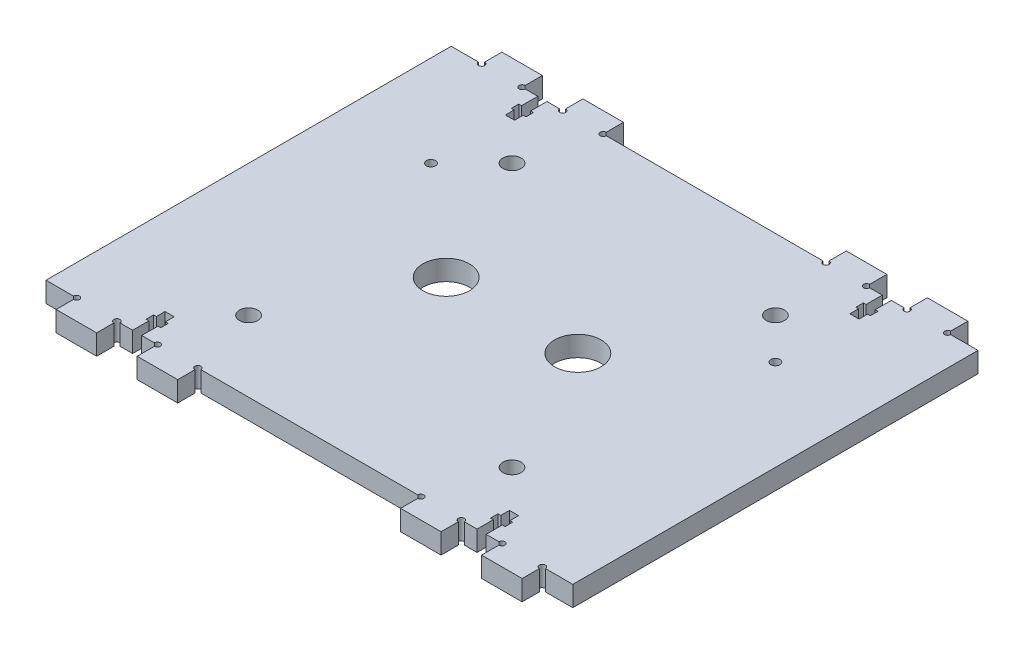
SolidWorks part; units mm, degrees
material "POLICARB. TRANSP."
ref_plane "Front Plane" through (0, 0, 0) normal (0, 0, 1) x (1, 0, 0)
ref_plane "Top Plane" through (0, 0, 0) normal (0, 1, 0) x (1, 0, 0)
ref_plane "Right Plane" through (0, 0, 0) normal (1, 0, 0) x (0, 0, -1)
sketch "Sketch1" plane through (0, 0, 0) normal (0, 1, 0) x (1, 0, 0)
  line L1 (130, 100) -> (-130, 100)
  line L2 (130, 100) -> (130, -100)
  line L3 (130, -100) -> (-130, -100)
  line L4 (-130, 100) -> (-130, -100)
  line L5 (0, -100) -> (0, 100) construction
  line L6 (130, 0) -> (-130, 0) construction
  point P0 (0, 0)
  dimension "D1" = 200
  dimension "D2" = 260
extrude "Extrude1" add sketch "Sketch1" along normal blind 10
sketch "Sketch3" plane through (0, 10, 0) normal (0, 1, 0) x (1, 0, 0)
  line L0 (130, 100) -> (-130, 100) construction
  line L1 (-115, 50) -> (-95, 50)
  line L2 (-115, 50) -> (-115, 40)
  line L3 (-115, 40) -> (-95, 40)
  line L4 (-95, 50) -> (-95, 40)
  line L9 (95, 50) -> (115, 50)
  line L10 (95, 50) -> (95, 40)
  line L11 (95, 40) -> (115, 40)
  line L12 (115, 50) -> (115, 40)
  line L13 (0, 0) -> (0, -100) construction
  line L14 (-130, -100) -> (130, -100) construction
  line L15 (-130, 100) -> (-130, -100) construction
  line L17 (-75, 50) -> (-55, 50)
  line L18 (-75, 50) -> (-75, 40)
  line L19 (-75, 40) -> (-55, 40)
  line L20 (-55, 50) -> (-55, 40)
  line L21 (55, 50) -> (75, 50)
  line L22 (55, 50) -> (55, 40)
  line L23 (55, 40) -> (75, 40)
  line L24 (75, 50) -> (75, 40)
  dimension "D1" = 50
  dimension "D2" = 20
  dimension "D3" = 10
  dimension "D4" = 15
  dimension "D5" = 20
  dimension "D6" = 10
  dimension "D7" = 20
extrude "Extrude2" [suppressed] cut sketch "Sketch3" against normal blind 10
hole_wizard "M4 Clearance Hole1" positions "Sketch4" profile "Sketch5" hole size "M4" standard "DIN" end condition through all
sketch "Sketch4" plane through (0, 10, 0) normal (0, 1, 0) x (1, 0, 0)
  line L0 (0, 0) -> (0, 100) construction
  line L8 (130, 100) -> (-130, 100) construction
  line L14 (-130, 100) -> (-130, -100) construction
  point P0 (-85, 45)
  point P2 (85, 45)
  point P44 (0, 0)
  dimension "D1" = 45
  dimension "D2" = 55
sketch "Sketch5" plane through (-85, 10, -45) normal (1, 0, 0) x (0, 0, 1)
  line L0 (0, 0) -> (0, 10)
  line L1 (0, 10) -> (2.25, 10)
  line L2 (2.25, 10) -> (2.25, 0)
  line L5 (2.25, 0) -> (0, 0)
  line L11 (0, -6.35) -> (0, 107.95) construction
  dimension "Thru Hole Dia." = 4.5
  dimension "Thru Hole Depth" = 10
sketch "Sketch6" [suppressed] plane through (0, 10, 0) normal (0, 1, 0) x (1, 0, 0)
  line L0 (-113.5, 50) -> (-115, 50)
  line L1 (-115, 50) -> (-115, 48.5)
  line L2 (-113.5, 40) -> (-115, 40)
  line L3 (-115, 40) -> (-115, 41.5)
  arc A0 (-115, 41.5) -> (-113.5, 40) centre (-115, 40) ccw
  arc A1 (-113.5, 50) -> (-115, 48.5) centre (-115, 50) ccw
  dimension "D1" = 3
extrude "Extrude3" [suppressed] cut sketch "Sketch6" against normal blind 10
ref_plane "Plane1" [suppressed] through (-105, 0, 0) normal (1, 0, 0) x (0, 0, -1)
mirror "Mirror1" [suppressed] about plane through (-105, 0, 0) normal (1, 0, 0)
ref_plane "Plane2" [suppressed] through (-85, 0, 0) normal (-1, 0, 0) x (0, 0, 1)
mirror "Mirror2" [suppressed] about plane through (-85, 0, 0) normal (-1, 0, 0)
ref_plane "Plane3" through (0, 0, 0) normal (1, 0, 0) x (0, 0, -1)
mirror "Mirror3" [suppressed] about plane through (0, 0, 0) normal (1, 0, 0)
sketch "Sketch7" plane through (0, 10, 0) normal (0, 1, 0) x (1, 0, 0)
  line L0 (-130, -100) -> (130, -100) construction
  line L1 (-115, -100) -> (-95, -100)
  line L2 (-115, -100) -> (-115, -110)
  line L3 (-115, -110) -> (-95, -110)
  line L4 (-95, -100) -> (-95, -110)
  line L5 (-130, 100) -> (-130, -100) construction
  line L6 (-75, -100) -> (-55, -100)
  line L7 (-75, -100) -> (-75, -110)
  line L8 (-75, -110) -> (-55, -110)
  line L9 (-55, -100) -> (-55, -110)
  dimension "D1" = 20
  dimension "D2" = 15
  dimension "D3" = 20
  dimension "D4" = 10
extrude "Extrude4" add sketch "Sketch7" against normal blind 10
pattern_linear "LPattern1" count 2 spacing 170 along (1, 0, 0) count 2 spacing 210 along (0, 0, -1) of "Extrude4"
sketch "Sketch8" plane through (0, 10, 0) normal (0, 1, 0) x (1, 0, 0)
  line L0 (-116.5, -100) -> (-115, -100)
  line L1 (-115, -100) -> (-115, -101.5)
  line L3 (-95, -101.5) -> (-95, -100)
  line L4 (-95, -100) -> (-93.5, -100)
  line L5 (-75, -100) -> (-75, -101.5)
  line L7 (-55, -101.5) -> (-55, -100)
  line L8 (-55, -100) -> (-53.5, -100)
  line L9 (-55, -110) -> (-55, -100) construction
  line L10 (-76.5, -100) -> (-75, -100)
  arc A0 (-115, -101.5) -> (-116.5, -100) centre (-115, -100) ccw
  arc A1 (-93.5, -100) -> (-95, -101.5) centre (-95, -100) ccw
  arc A2 (-75, -101.5) -> (-76.5, -100) centre (-75, -100) ccw
  arc A3 (-53.5, -100) -> (-55, -101.5) centre (-55, -100) ccw
  dimension "D1" = 3
extrude "Extrude5" cut sketch "Sketch8" against normal blind 10
ref_plane "Plane4" through (0, 0, 0) normal (1, 0, 0) x (0, 0, -1)
ref_plane "Plane5" through (0, 0, 0) normal (0, 0, 1) x (1, 0, 0)
mirror "Mirror4" about plane through (0, 0, 0) normal (1, 0, 0) of "Extrude5"
mirror "Mirror5" about plane through (0, 0, 0) normal (0, 0, 1) of "Extrude5", "Mirror4"
sketch "Sketch9" plane through (0, 10, 0) normal (0, 1, 0) x (1, 0, 0)
  line L0 (-95, -105.75) -> (-75, -105.75) construction
  line L1 (-95, -110) -> (-95, -101.5) construction
  line L2 (-75, -101.5) -> (-75, -110) construction
  line L3 (-87.25, -100) -> (-87.25, -92)
  line L4 (-93.5, -100) -> (-76.5, -100) construction
  line L5 (-87.25, -92) -> (-88.625, -92)
  line L6 (-88.625, -92) -> (-88.625, -88.3)
  line L7 (-88.625, -88.3) -> (-87.25, -88.3)
  line L8 (-87.25, -88.3) -> (-87.25, -84)
  line L9 (-87.25, -84) -> (-82.75, -84)
  line L10 (-82.75, -84) -> (-82.75, -88.3)
  line L11 (-82.75, -88.3) -> (-81.375, -88.3)
  line L12 (-81.375, -88.3) -> (-81.375, -92)
  line L13 (-81.375, -92) -> (-82.75, -92)
  line L14 (-82.75, -92) -> (-82.75, -100)
  line L15 (-85, -105.75) -> (-85, -100) construction
  line L16 (-87.25, -100) -> (-82.75, -100)
  dimension "D1" = 16
  dimension "D2" = 8
  dimension "D3" = 4.5
  dimension "D4" = 7.25
  dimension "D5" = 3.7
extrude "Extrude6" cut sketch "Sketch9" against normal blind 10
mirror "Mirror6" about plane through (0, 0, 0) normal (1, 0, 0) of "Extrude6"
mirror "Mirror7" about plane through (0, 0, 0) normal (0, 0, 1) of "Mirror6", "Extrude6"
sketch "Sketch10" plane through (0, 10, 0) normal (0, 1, 0) x (1, 0, 0)
  line L0 (0, 0) -> (0, -100) construction
  line L1 (-53.5, -100) -> (53.5, -100) construction
  circle A0 centre (-32.5, 0) radius 11.5
  circle A1 centre (32.5, 0) radius 11.5
  dimension "D1" = 23
  dimension "D2" = 65
extrude "Extrude7" cut sketch "Sketch10" against normal blind 10
hole_wizard "M8 Clearance Hole1" positions "Sketch11" profile "Sketch12" hole size "M8" standard "DIN" end condition through all
sketch "Sketch11" plane through (0, 10, 0) normal (0, 1, 0) x (1, 0, 0)
  line L0 (0, -100) -> (0, 0) construction
  line L1 (-53.5, -100) -> (53.5, -100) construction
  line L2 (0, 0) -> (130, 0) construction
  line L3 (130, -100) -> (130, 100) construction
  point P0 (-65, 65)
  point P2 (65, 65)
  point P4 (65, -65)
  point P6 (-65, -65)
  dimension "D1" = 130
  dimension "D2" = 130
sketch "Sketch12" plane through (-65, 10, -65) normal (1, 0, 0) x (0, 0, 1)
  line L0 (0, 0) -> (0, 10)
  line L1 (0, 10) -> (4.5, 10)
  line L2 (4.5, 10) -> (4.5, 0)
  line L5 (4.5, 0) -> (0, 0)
  line L11 (0, -6.35) -> (0, 107.95) construction
  dimension "Thru Hole Dia." = 9
  dimension "Thru Hole Depth" = 10
